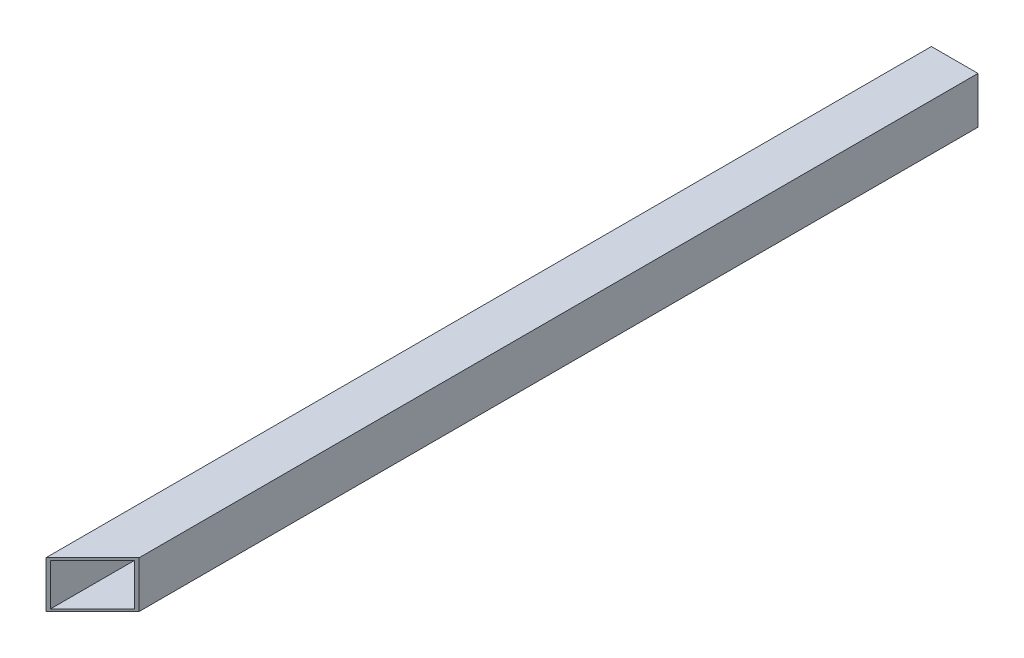
SolidWorks part; units mm, degrees
ref_plane "Front Plane" through (0, 0, 0) normal (0, 0, 1) x (1, 0, 0)
ref_plane "Top Plane" through (0, 0, 0) normal (0, 1, 0) x (1, 0, 0)
ref_plane "Right Plane" through (0, 0, 0) normal (1, 0, 0) x (0, 0, -1)
sketch "Sketch3" plane through (0, 0, 0) normal (0, 0, 1) x (1, 0, 0)
  line L1 (-12.7, -12.7) -> (12.7, -12.7)
  line L2 (-12.7, -12.7) -> (-12.7, 12.7)
  line L3 (-12.7, 12.7) -> (12.7, 12.7)
  line L4 (12.7, -12.7) -> (12.7, 12.7)
  line L5 (-12.7, -12.7) -> (12.7, 12.7) construction
  line L6 (-12.7, 12.7) -> (12.7, -12.7) construction
  line L7 (-11.4554, 11.4554) -> (11.4554, 11.4554)
  line L8 (-11.4554, 11.4554) -> (-11.4554, -11.4554)
  line L9 (-11.4554, -11.4554) -> (11.4554, -11.4554)
  line L10 (11.4554, 11.4554) -> (11.4554, -11.4554)
  line L11 (-11.4554, 11.4554) -> (11.4554, -11.4554) construction
  line L12 (-11.4554, -11.4554) -> (11.4554, 11.4554) construction
  point P0 (0, 0)
  point P6 (0, 0)
  dimension "D1" = 25.4
  dimension "D2" = 25.4
  dimension "D3" = 22.9108
  dimension "D4" = 22.9108
extrude "Boss-Extrude1" add sketch "Sketch3" along normal blind 482.6
ref_plane "Plane1" through (-247.65, 0, 247.65) normal (-0.7071, 0, 0.7071) x (0, -1, 0)
sketch "Sketch4" plane through (-247.65, 0, 247.65) normal (-0.7071, 0, 0.7071) x (0, -1, 0)
  line L1 (-12.7, 332.2695) -> (12.7, 332.2695)
  line L2 (-12.7, 332.2695) -> (-12.7, 357.6695)
  line L3 (-12.7, 357.6695) -> (12.7, 357.6695)
  line L4 (12.7, 332.2695) -> (12.7, 357.6695)
  dimension "D1" = 25.4
  dimension "D2" = 25.4
extrude "Cut-Extrude1" cut sketch "Sketch4" against normal blind 482.6
